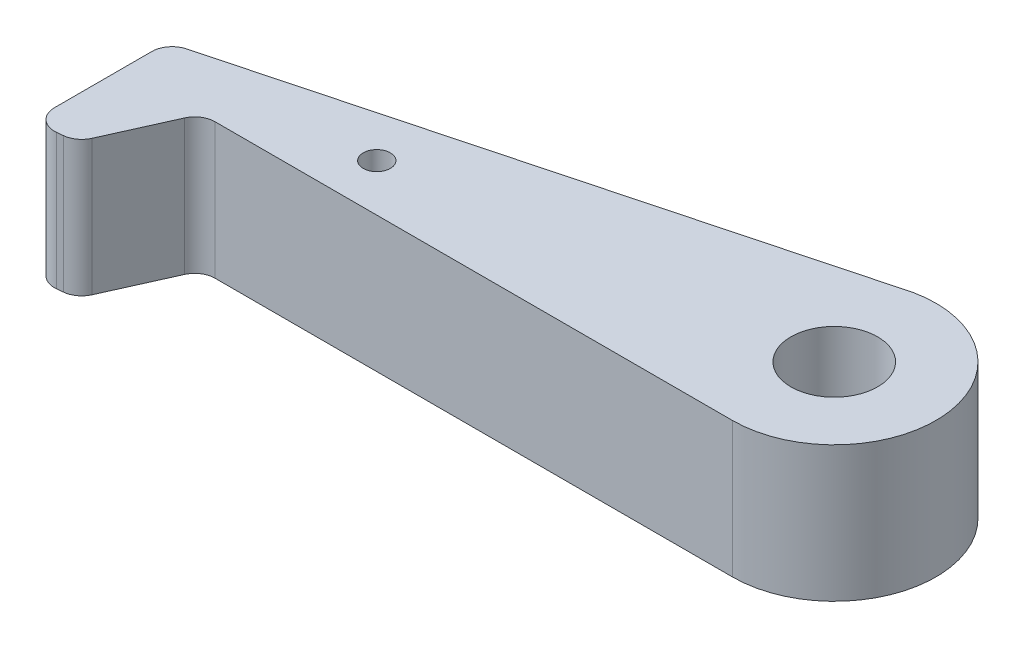
SolidWorks part; units mm, degrees
ref_plane "Front Plane" through (0, 0, 0) normal (0, 0, 1) x (1, 0, 0)
ref_plane "Top Plane" through (0, 0, 0) normal (0, 1, 0) x (1, 0, 0)
ref_plane "Right Plane" through (0, 0, 0) normal (1, 0, 0) x (0, 0, -1)
sketch "Sketch1" plane through (0, 0, 0) normal (0, 1, 0) x (1, 0, 0)
  line L0 (0, 0) -> (0, 35) construction
  line L1 (0, 0) -> (26.4503, 36.4058) construction
  line L2 (0, 35) -> (24.8062, 37.5454) construction
  line L3 (0, 35) -> (0, 45) construction
  line L5 (0, 45) -> (43.4948, 56.5414)
  line L6 (0, 45) -> (0, 35)
  line L7 (0, 35) -> (2.9843, 35.3062)
  line L8 (2.9843, 35.3062) -> (5.8473, 41.694)
  line L9 (5.8473, 41.694) -> (45, 41.694)
  line L10 (5.8473, 41.694) -> (0, 41.694) construction
  line L11 (45, 49.194) -> (14.0055, 45.0034) construction
  circle A0 centre (0, 0) radius 45 construction
  circle A1 centre (0, 0) radius 35 construction
  arc A3 (43.4948, 56.5414) -> (45, 41.694) centre (45, 49.194) cw
  circle A4 centre (45, 49.194) radius 3.2
  circle A5 centre (15.2705, 45.1744) radius 1
  circle A6 centre (24.8015, 91.4456) radius 1.25 construction
  circle A7 centre (24.8015, 91.4456) radius 1.25
  point P17 (16.5212, 45.3435)
  dimension "D1" = 90
  dimension "D2" = 70
  dimension "D12" = 6.4
  dimension "D13" = 2
  dimension "D8" = 7.5
  dimension "D15" = 30
  dimension "D3" = 36
  dimension "D4" = 2
  dimension "D5" = 45
  dimension "D6" = 3
  dimension "D7" = 7
  dimension "D9" = 45
  dimension "D10" = 60
  dimension "D11" = 45
  dimension "D14" = 7.7
extrude "Boss-Extrude1" add sketch "Sketch1" along normal blind 10 contours A3 L5 L6 L7 L8 L9 A4
fillet "Fillet1" radius 1.5 4 edges at (0, 5, -45) (0, 5, -35) (2.9843, 5, -35.3062) (5.8473, 5, -41.694)
